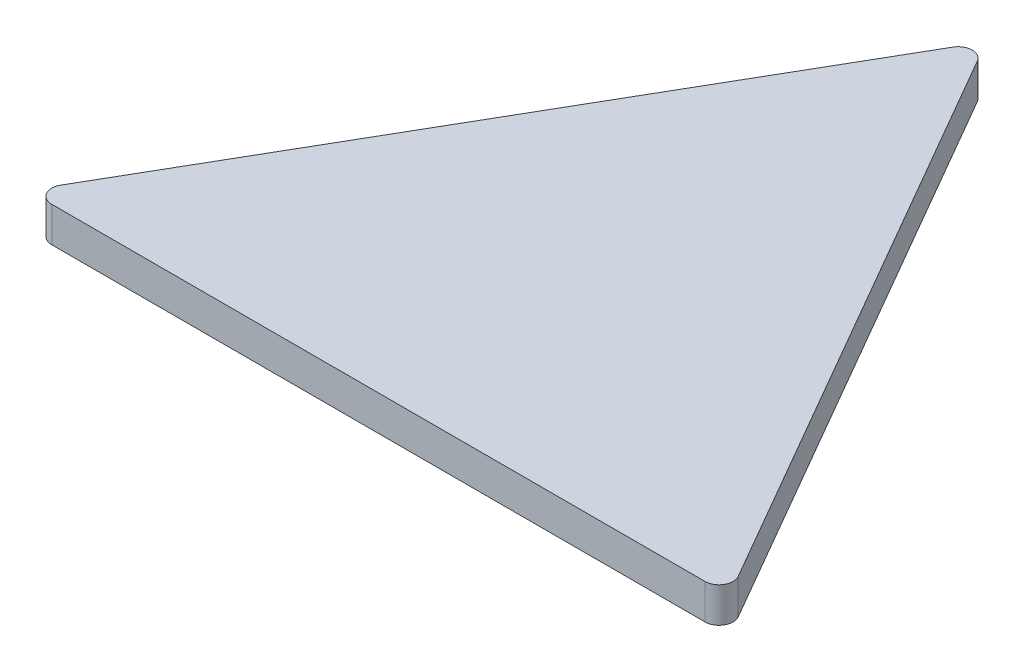
SolidWorks part; units mm, degrees
ref_plane "Front Plane" through (0, 0, 0) normal (0, 0, 1) x (1, 0, 0)
ref_plane "Top Plane" through (0, 0, 0) normal (0, 1, 0) x (1, 0, 0)
ref_plane "Right Plane" through (0, 0, 0) normal (1, 0, 0) x (0, 0, -1)
sketch "Sketch1" plane through (0, 0, 0) normal (0, 1, 0) x (1, 0, 0)
  line L1 (0, 146.647) -> (-127, -73.3235)
  line L2 (-127, -73.3235) -> (127, -73.3235)
  line L3 (127, -73.3235) -> (0, 146.647)
  circle A0 centre (0, 0) radius 73.3235 construction
  dimension "D1" = 254
extrude "Boss-Extrude1" add sketch "Sketch1" along normal blind 12.7
fillet "Fillet1" radius 5.08 3 edges at (0, 6.35, -146.647) (127, 6.35, 73.3235) (-127, 6.35, 73.3235)
